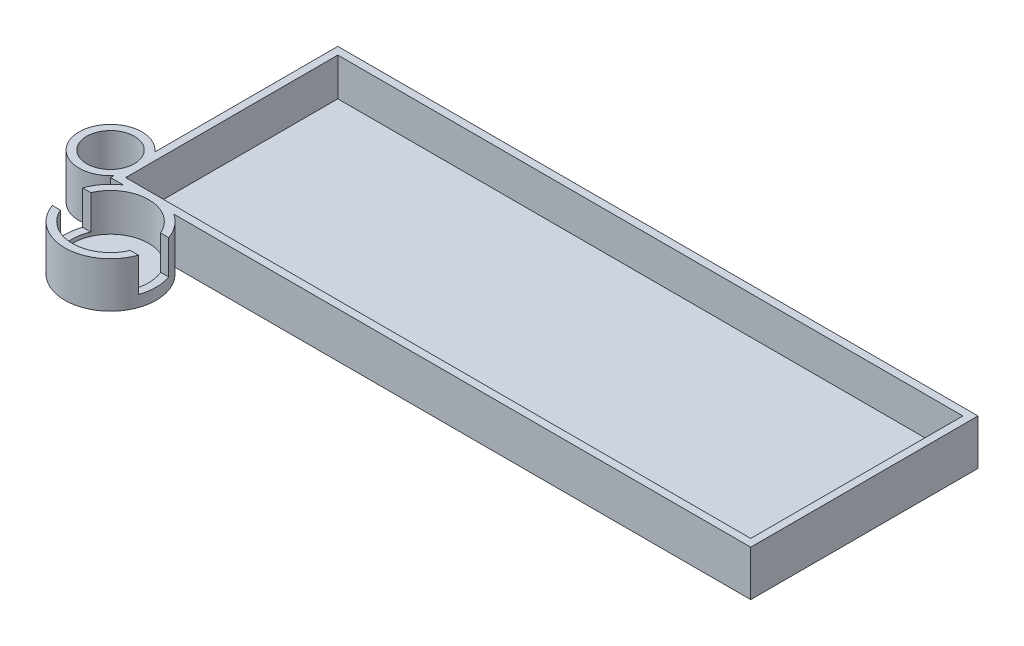
SolidWorks part; units mm, degrees
ref_plane "前视基准面" through (0, 0, 0) normal (0, 0, 1) x (1, 0, 0)
ref_plane "上视基准面" through (0, 0, 0) normal (0, 1, 0) x (1, 0, 0)
ref_plane "右视基准面" through (0, 0, 0) normal (1, 0, 0) x (0, 0, -1)
other "Configuration Table"
sketch "草图1" plane through (0, 0, 0) normal (0, 1, 0) x (1, 0, 0)
  line L1 (0, 0) -> (165, 0)
  line L2 (0, 0) -> (0, -56)
  line L3 (0, -56) -> (165, -56)
  line L4 (165, 0) -> (165, -56)
extrude "凸台-拉伸1" add sketch "草图1" along normal blind 2
sketch "草图3" plane through (0, 0, 0) normal (0, -1, 0) x (1, 0, 0)
  line L0 (-2, 58) -> (-2, -2)
  line L1 (0, 56) -> (165, 56)
  line L2 (0, 56) -> (0, 0)
  line L3 (0, 0) -> (165, 0)
  line L4 (165, 56) -> (165, 0)
  line L5 (-2, -2) -> (167, -2)
  line L6 (167, 58) -> (167, -2)
  line L7 (-2, 58) -> (167, 58)
  dimension "D1" = 2
extrude "凸台-拉伸2" add sketch "草图3" against normal blind 12
sketch "草图4" plane through (0, 0, 0) normal (0, -1, 0) x (1, 0, 0)
  line L0 (167, 58) -> (-2, 58) construction
  line L1 (-2, 58) -> (-2, -2) construction
  circle A0 centre (8.05, 68.05) radius 10.05
  point P4 (0, 0)
  point P5 (12.2672, 68.1691)
extrude "凸台-拉伸3" add sketch "草图4" against normal blind 2 separate body contours A0
sketch "草图5" plane through (0, 0, 0) normal (0, -1, 0) x (1, 0, 0)
  circle A0 centre (8.05, 68.05) radius 10.05
  circle A1 centre (8.05, 68.05) radius 12.05
  dimension "D1" = 2
extrude "凸台-拉伸4" add sketch "草图5" against normal blind 12
sketch "草图6" plane through (0, 12, 0) normal (0, 1, 0) x (1, 0, 0)
  line L0 (31.2665, -72.05) -> (-15.1665, -72.05)
  line L1 (31.2665, -72.05) -> (31.2665, -64.05)
  line L2 (-15.1665, -72.05) -> (-15.1665, -64.05)
  line L3 (31.2665, -64.05) -> (-15.1665, -64.05)
  line L4 (-15.1665, -68.05) -> (31.2665, -68.05) construction
  line L5 (8.05, -72.05) -> (8.05, -64.05) construction
  point P0 (108.7335, -72.5904)
  point P1 (8.05, -68.05)
extrude "切除-拉伸1" cut sketch "草图6" against normal blind 9
sketch "草图7" plane through (0, 0, 0) normal (0, -1, 0) x (1, 0, 0)
  line L0 (-2, 58) -> (-2, -2) construction
  line L2 (1.4017, 58) -> (-2, 58) construction
  circle A0 centre (-8.3, 51.7) radius 6.3
extrude "凸台-拉伸5" add sketch "草图7" against normal blind 2 separate body contours A0
sketch "草图8" plane through (0, 0, 0) normal (0, -1, 0) x (1, 0, 0)
  circle A2 centre (-8.3, 51.7) radius 8.3
  circle A3 centre (-8.3, 51.7) radius 8.3
  circle M2 centre (-8.3, 51.7) radius 6.3
  dimension "D1" = 2
extrude "凸台-拉伸6" add sketch "草图8" against normal blind 12 contours A3 M2
